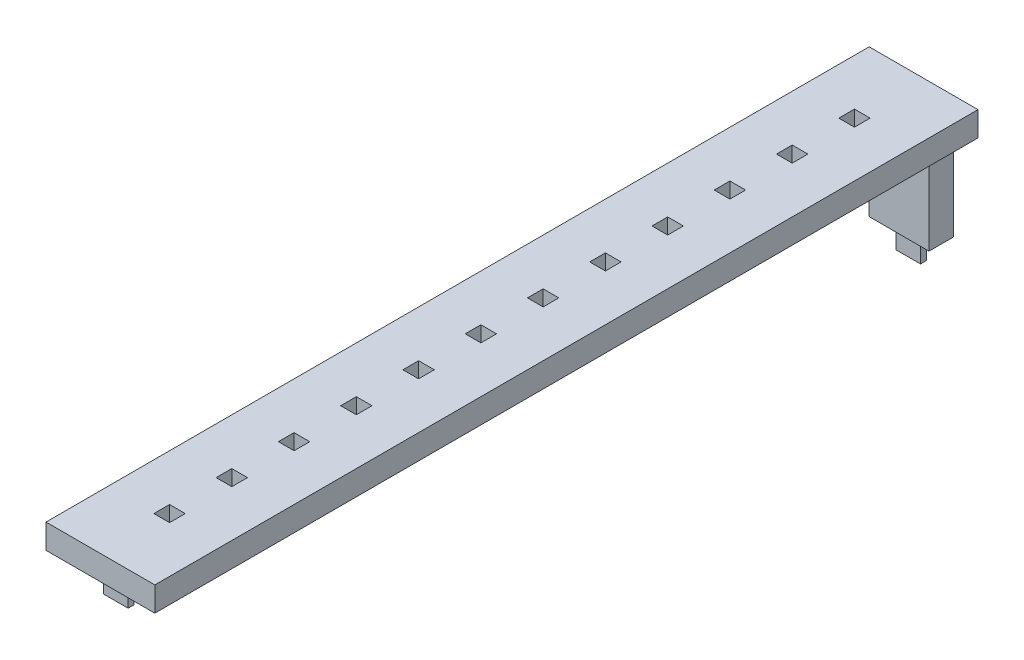
SolidWorks part; units mm, degrees
material "PP Kopolimer"
ref_plane "Front Plane" through (0, 0, 0) normal (0, 0, 1) x (1, 0, 0)
ref_plane "Top Plane" through (0, 0, 0) normal (0, 1, 0) x (1, 0, 0)
ref_plane "Right Plane" through (0, 0, 0) normal (1, 0, 0) x (0, 0, -1)
sketch "Szkic1" plane through (0, 0, 0) normal (0, 1, 0) x (1, 0, 0)
  line L1 (-2.22, -16.79) -> (2.22, -16.79)
  line L2 (-2.22, -16.79) -> (-2.22, 16.79)
  line L3 (-2.22, 16.79) -> (2.22, 16.79)
  line L4 (2.22, -16.79) -> (2.22, 16.79)
  line L5 (-2.22, -16.79) -> (2.22, 16.79) construction
  line L6 (-2.22, 16.79) -> (2.22, -16.79) construction
  point P0 (0, 0)
  dimension "D1" = 33.58
  dimension "D2" = 4.44
extrude "Dodanie-wyciągnięcie1" add sketch "Szkic1" along normal blind 1
sketch "Szkic2" plane through (0, 1, 0) normal (0, 1, 0) x (1, 0, 0)
  line L0 (0, -16.79) -> (0, -14.29) construction
  line L1 (-2.22, -16.79) -> (2.22, -16.79) construction
  line L2 (0, -14.29) -> (0, -13.65) construction
  line L3 (0, -13.65) -> (0, -11.75) construction
  line L4 (0, -11.75) -> (0, -11.11) construction
  line L5 (0, -11.11) -> (0, -9.21) construction
  line L6 (0, -9.21) -> (0, -8.57) construction
  line L7 (0, -8.57) -> (0, -6.67) construction
  line L8 (0, -6.67) -> (0, -6.03) construction
  line L9 (0, -6.03) -> (0, -4.13) construction
  line L10 (0, -4.13) -> (0, -3.49) construction
  line L11 (0, -3.49) -> (0, -1.59) construction
  line L12 (0, -1.59) -> (0, -0.95) construction
  line L13 (0, -0.95) -> (0, 0.95) construction
  line L14 (0, 0.95) -> (0, 1.59) construction
  line L15 (0, 1.59) -> (0, 3.49) construction
  line L16 (0, 3.49) -> (0, 4.13) construction
  line L17 (0, 4.13) -> (0, 6.03) construction
  line L18 (0, 6.03) -> (0, 6.67) construction
  line L19 (0, 6.67) -> (0, 8.57) construction
  line L20 (0, 8.57) -> (0, 9.21) construction
  line L21 (0, 9.21) -> (0, 11.11) construction
  line L22 (0, 11.11) -> (0, 11.75) construction
  line L23 (0, 11.75) -> (0, 13.65) construction
  line L24 (0, 13.65) -> (0, 14.29) construction
  line L25 (0, 14.29) -> (0, 16.79) construction
  line L26 (2.22, 16.79) -> (-2.22, 16.79) construction
  line L28 (0.32, -14.29) -> (-0.32, -14.29)
  line L29 (0.32, -14.29) -> (0.32, -13.65)
  line L30 (0.32, -13.65) -> (-0.32, -13.65)
  line L31 (-0.32, -14.29) -> (-0.32, -13.65)
  line L32 (0.32, -14.29) -> (-0.32, -13.65) construction
  line L33 (0.32, -13.65) -> (-0.32, -14.29) construction
  line L34 (0.32, -11.75) -> (-0.32, -11.75)
  line L35 (0.32, -11.75) -> (0.32, -11.11)
  line L36 (0.32, -11.11) -> (-0.32, -11.11)
  line L37 (-0.32, -11.75) -> (-0.32, -11.11)
  line L38 (0.32, -11.75) -> (-0.32, -11.11) construction
  line L39 (0.32, -11.11) -> (-0.32, -11.75) construction
  line L40 (0.32, -9.21) -> (-0.32, -9.21)
  line L41 (0.32, -9.21) -> (0.32, -8.57)
  line L42 (0.32, -8.57) -> (-0.32, -8.57)
  line L43 (-0.32, -9.21) -> (-0.32, -8.57)
  line L44 (0.32, -9.21) -> (-0.32, -8.57) construction
  line L45 (0.32, -8.57) -> (-0.32, -9.21) construction
  line L46 (0.32, -6.67) -> (-0.32, -6.67)
  line L47 (0.32, -6.67) -> (0.32, -6.03)
  line L48 (0.32, -6.03) -> (-0.32, -6.03)
  line L49 (-0.32, -6.67) -> (-0.32, -6.03)
  line L50 (0.32, -6.67) -> (-0.32, -6.03) construction
  line L51 (0.32, -6.03) -> (-0.32, -6.67) construction
  line L52 (0.32, -4.13) -> (-0.32, -4.13)
  line L53 (0.32, -4.13) -> (0.32, -3.49)
  line L54 (0.32, -3.49) -> (-0.32, -3.49)
  line L55 (-0.32, -4.13) -> (-0.32, -3.49)
  line L56 (0.32, -4.13) -> (-0.32, -3.49) construction
  line L57 (0.32, -3.49) -> (-0.32, -4.13) construction
  line L58 (0.32, -1.59) -> (-0.32, -1.59)
  line L59 (0.32, -1.59) -> (0.32, -0.95)
  line L60 (0.32, -0.95) -> (-0.32, -0.95)
  line L61 (-0.32, -1.59) -> (-0.32, -0.95)
  line L62 (0.32, -1.59) -> (-0.32, -0.95) construction
  line L63 (0.32, -0.95) -> (-0.32, -1.59) construction
  line L64 (0.32, 0.95) -> (-0.32, 0.95)
  line L65 (0.32, 0.95) -> (0.32, 1.59)
  line L66 (0.32, 1.59) -> (-0.32, 1.59)
  line L67 (-0.32, 0.95) -> (-0.32, 1.59)
  line L68 (0.32, 0.95) -> (-0.32, 1.59) construction
  line L69 (0.32, 1.59) -> (-0.32, 0.95) construction
  line L70 (0.32, 3.49) -> (-0.32, 3.49)
  line L71 (0.32, 3.49) -> (0.32, 4.13)
  line L72 (0.32, 4.13) -> (-0.32, 4.13)
  line L73 (-0.32, 3.49) -> (-0.32, 4.13)
  line L74 (0.32, 3.49) -> (-0.32, 4.13) construction
  line L75 (0.32, 4.13) -> (-0.32, 3.49) construction
  line L76 (0.32, 6.03) -> (-0.32, 6.03)
  line L77 (0.32, 6.03) -> (0.32, 6.67)
  line L78 (0.32, 6.67) -> (-0.32, 6.67)
  line L79 (-0.32, 6.03) -> (-0.32, 6.67)
  line L80 (0.32, 6.03) -> (-0.32, 6.67) construction
  line L81 (0.32, 6.67) -> (-0.32, 6.03) construction
  line L82 (0.32, 8.57) -> (-0.32, 8.57)
  line L83 (0.32, 8.57) -> (0.32, 9.21)
  line L84 (0.32, 9.21) -> (-0.32, 9.21)
  line L85 (-0.32, 8.57) -> (-0.32, 9.21)
  line L86 (0.32, 8.57) -> (-0.32, 9.21) construction
  line L87 (0.32, 9.21) -> (-0.32, 8.57) construction
  line L88 (0.32, 11.11) -> (-0.32, 11.11)
  line L89 (0.32, 11.11) -> (0.32, 11.75)
  line L90 (0.32, 11.75) -> (-0.32, 11.75)
  line L91 (-0.32, 11.11) -> (-0.32, 11.75)
  line L92 (0.32, 11.11) -> (-0.32, 11.75) construction
  line L93 (0.32, 11.75) -> (-0.32, 11.11) construction
  line L94 (0.32, 13.65) -> (-0.32, 13.65)
  line L95 (0.32, 13.65) -> (0.32, 14.29)
  line L96 (0.32, 14.29) -> (-0.32, 14.29)
  line L97 (-0.32, 13.65) -> (-0.32, 14.29)
  line L98 (0.32, 13.65) -> (-0.32, 14.29) construction
  line L99 (0.32, 14.29) -> (-0.32, 13.65) construction
  point P31 (0, -13.97)
  point P36 (0, -11.43)
  point P41 (0, -8.89)
  point P46 (0, -6.35)
  point P51 (0, -3.81)
  point P56 (0, -1.27)
  point P61 (0, 1.27)
  point P66 (0, 3.81)
  point P71 (0, 6.35)
  point P76 (0, 8.89)
  point P81 (0, 11.43)
  point P86 (0, 13.97)
extrude "Wytnij-wyciągnięcie1" cut sketch "Szkic2" against normal blind 1
sketch "Szkic3" plane through (0, 0, 0) normal (0, -1, 0) x (1, 0, 0)
  line L0 (0, 16.79) -> (0, 15.28) construction
  line L1 (-2.22, 16.79) -> (2.22, 16.79) construction
  line L3 (-0.5, 16.16) -> (0.5, 16.16)
  line L4 (-0.5, 16.16) -> (-0.5, 15.91)
  line L5 (-0.5, 15.91) -> (0.5, 15.91)
  line L6 (0.5, 16.16) -> (0.5, 15.91)
  line L7 (-0.5, 16.16) -> (0.5, 15.91) construction
  line L8 (-0.5, 15.91) -> (0.5, 16.16) construction
  point P5 (0, 16.035)
  dimension "D1" = 1
  dimension "D2" = 0.25
extrude "Dodanie-wyciągnięcie2" add sketch "Szkic3" along normal blind 1
sketch "Szkic4" plane through (0, 0, 0) normal (0, -1, 0) x (1, 0, 0)
  line L0 (-2.22, -16.79) -> (-2.22, 16.79) construction
  line L1 (2.22, -16.79) -> (-2.22, -16.79)
  line L2 (2.22, -16.79) -> (2.22, -15.79)
  line L3 (2.22, -15.79) -> (-2.22, -15.79)
  line L4 (-2.22, -16.79) -> (-2.22, -15.79)
extrude "Dodanie-wyciągnięcie3" add sketch "Szkic4" along normal blind 4
sketch "Szkic5" plane through (0, -4, 0) normal (0, -1, 0) x (1, 0, 0)
  line L0 (0, -15.79) -> (0, -16.79) construction
  line L1 (2.22, -15.79) -> (-2.22, -15.79) construction
  line L2 (-2.22, -16.79) -> (2.22, -16.79) construction
  line L4 (-0.5, -16.165) -> (0.5, -16.165)
  line L5 (-0.5, -16.165) -> (-0.5, -16.415)
  line L6 (-0.5, -16.415) -> (0.5, -16.415)
  line L7 (0.5, -16.165) -> (0.5, -16.415)
  line L8 (-0.5, -16.165) -> (0.5, -16.415) construction
  line L9 (-0.5, -16.415) -> (0.5, -16.165) construction
  point P6 (0, -16.29)
extrude "Dodanie-wyciągnięcie4" add sketch "Szkic5" along normal blind 1
sketch "Szkic6" plane through (0, -4, 0) normal (0, -1, 0) x (1, 0, 0)
  line L0 (2.22, -15.79) -> (-2.22, -15.79) construction
  line L1 (2.22, -16.79) -> (1.22, -16.79)
  line L2 (2.22, -16.79) -> (2.22, -15.79)
  line L3 (2.22, -15.79) -> (1.22, -15.79)
  line L4 (1.22, -16.79) -> (1.22, -15.79)
  line L6 (-2.22, -16.79) -> (-1.22, -16.79)
  line L7 (-2.22, -16.79) -> (-2.22, -15.79)
  line L8 (-2.22, -15.79) -> (-1.22, -15.79)
  line L9 (-1.22, -16.79) -> (-1.22, -15.79)
extrude "Wytnij-wyciągnięcie2" cut sketch "Szkic6" against normal blind 4
